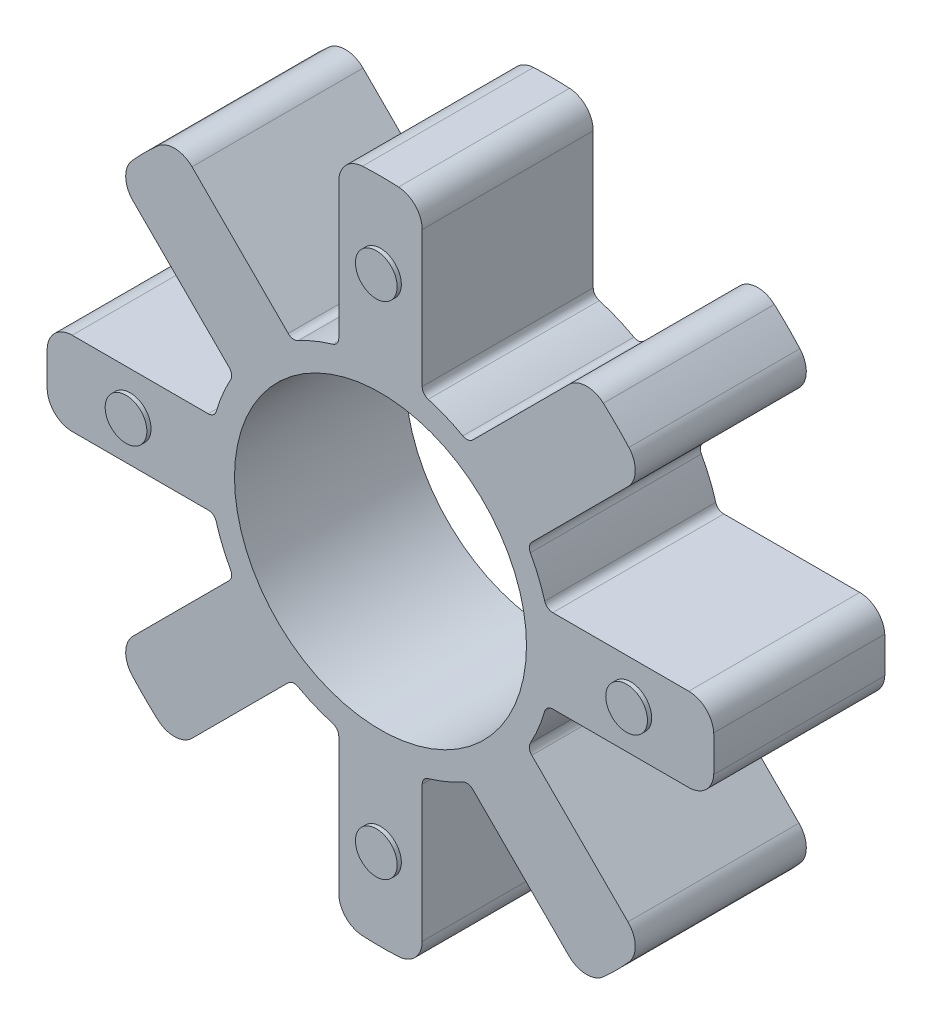
SolidWorks part; units mm, degrees
material "NEOPRENE"
ref_plane "Front Plane" through (0, 0, 0) normal (0, 0, 1) x (1, 0, 0)
ref_plane "Top Plane" through (0, 0, 0) normal (0, 1, 0) x (1, 0, 0)
ref_plane "Right Plane" through (0, 0, 0) normal (1, 0, 0) x (0, 0, -1)
sketch "Sketch1" plane through (0, 0, 0) normal (0, 0, 1) x (1, 0, 0)
  line L0 (-5, 20.6458) -> (-5, 36.9459)
  line L1 (5, 36.9459) -> (5, 20.6458)
  line L2 (0, 0) -> (0, 32.1317) construction
  line L3 (11.0633, 18.1343) -> (22.5892, 29.6602)
  line L4 (29.6602, 22.5892) -> (18.1343, 11.0633)
  line L5 (20.6458, 5) -> (36.9459, 5)
  line L6 (36.9459, -5) -> (20.6458, -5)
  line L7 (18.1343, -11.0633) -> (29.6602, -22.5892)
  line L8 (22.5892, -29.6602) -> (11.0633, -18.1343)
  line L9 (5, -20.6458) -> (5, -36.9459)
  line L10 (-5, -36.9459) -> (-5, -20.6458)
  line L11 (-11.0633, -18.1343) -> (-22.5892, -29.6602)
  line L12 (-29.6602, -22.5892) -> (-18.1343, -11.0633)
  line L13 (-20.6458, -5) -> (-36.9459, -5)
  line L14 (-36.9459, 5) -> (-20.6458, 5)
  line L15 (-18.1343, 11.0633) -> (-29.6602, 22.5892)
  line L16 (-22.5892, 29.6602) -> (-11.0633, 18.1343)
  line L17 (0, 0) -> (48.5575, 0) construction
  arc A0 (-39.9415, 2.1622) -> (-39.9415, -2.1622) centre (0, 0) ccw
  arc A1 (-17.9651, 9.8745) -> (-19.6856, 5.7209) centre (0, 0) ccw
  circle A2 centre (0, 0) radius 17.5
  arc A3 (-26.714, 29.7718) -> (-29.7718, 26.714) centre (0, 0) ccw
  arc A4 (2.1622, 39.9415) -> (-2.1622, 39.9415) centre (0, 0) ccw
  arc A5 (29.7718, 26.714) -> (26.714, 29.7718) centre (0, 0) ccw
  arc A6 (26.714, -29.7718) -> (29.7718, -26.714) centre (0, 0) ccw
  arc A7 (-2.1622, -39.9415) -> (2.1622, -39.9415) centre (0, 0) ccw
  arc A8 (-29.7718, -26.714) -> (-26.714, -29.7718) centre (0, 0) ccw
  arc A9 (39.9415, -2.1622) -> (39.9415, 2.1622) centre (0, 0) ccw
  arc A10 (-19.6856, -5.7209) -> (-17.9651, -9.8745) centre (0, 0) ccw
  arc A11 (-9.8745, -17.9651) -> (-5.7209, -19.6856) centre (0, 0) ccw
  arc A12 (5.7209, -19.6856) -> (9.8745, -17.9651) centre (0, 0) ccw
  arc A13 (17.9651, -9.8745) -> (19.6856, -5.7209) centre (0, 0) ccw
  arc A14 (19.6856, 5.7209) -> (17.9651, 9.8745) centre (0, 0) ccw
  arc A15 (9.8745, 17.9651) -> (5.7209, 19.6856) centre (0, 0) ccw
  arc A16 (-5.7209, 19.6856) -> (-9.8745, 17.9651) centre (0, 0) ccw
  arc A17 (-29.6602, 22.5892) -> (-29.7718, 26.714) centre (-27.5389, 24.7105) cw
  arc A18 (-22.5892, 29.6602) -> (-26.714, 29.7718) centre (-24.7105, 27.5389) ccw
  arc A19 (-36.9459, -5) -> (-39.9415, -2.1622) centre (-36.9459, -2) cw
  arc A20 (-36.9459, 5) -> (-39.9415, 2.1622) centre (-36.9459, 2) ccw
  arc A21 (-22.5892, -29.6602) -> (-26.714, -29.7718) centre (-24.7105, -27.5389) cw
  arc A22 (-29.6602, -22.5892) -> (-29.7718, -26.714) centre (-27.5389, -24.7105) ccw
  arc A23 (-5, -36.9459) -> (-2.1622, -39.9415) centre (-2, -36.9459) ccw
  arc A24 (5, -36.9459) -> (2.1622, -39.9415) centre (2, -36.9459) cw
  arc A25 (29.6602, -22.5892) -> (29.7718, -26.714) centre (27.5389, -24.7105) cw
  arc A26 (22.5892, -29.6602) -> (26.714, -29.7718) centre (24.7105, -27.5389) ccw
  arc A27 (36.9459, -5) -> (39.9415, -2.1622) centre (36.9459, -2) ccw
  arc A28 (36.9459, 5) -> (39.9415, 2.1622) centre (36.9459, 2) cw
  arc A29 (29.6602, 22.5892) -> (29.7718, 26.714) centre (27.5389, 24.7105) ccw
  arc A30 (22.5892, 29.6602) -> (26.714, 29.7718) centre (24.7105, 27.5389) cw
  arc A31 (5, 36.9459) -> (2.1622, 39.9415) centre (2, 36.9459) ccw
  arc A32 (-5, 36.9459) -> (-2.1622, 39.9415) centre (-2, 36.9459) cw
  arc A33 (-11.0633, 18.1343) -> (-9.8745, 17.9651) centre (-10.3562, 18.8414) ccw
  arc A34 (-5, 20.6458) -> (-5.7209, 19.6856) centre (-6, 20.6458) cw
  arc A35 (11.0633, 18.1343) -> (9.8745, 17.9651) centre (10.3562, 18.8414) cw
  arc A36 (5, 20.6458) -> (5.7209, 19.6856) centre (6, 20.6458) ccw
  arc A37 (20.6458, 5) -> (19.6856, 5.7209) centre (20.6458, 6) cw
  arc A38 (18.1343, 11.0633) -> (17.9651, 9.8745) centre (18.8414, 10.3562) ccw
  arc A39 (18.1343, -11.0633) -> (17.9651, -9.8745) centre (18.8414, -10.3562) cw
  arc A40 (20.6458, -5) -> (19.6856, -5.7209) centre (20.6458, -6) ccw
  arc A41 (11.0633, -18.1343) -> (9.8745, -17.9651) centre (10.3562, -18.8414) ccw
  arc A42 (5, -20.6458) -> (5.7209, -19.6856) centre (6, -20.6458) cw
  arc A43 (-5, -20.6458) -> (-5.7209, -19.6856) centre (-6, -20.6458) ccw
  arc A44 (-11.0633, -18.1343) -> (-9.8745, -17.9651) centre (-10.3562, -18.8414) cw
  arc A45 (-18.1343, -11.0633) -> (-17.9651, -9.8745) centre (-18.8414, -10.3562) ccw
  arc A46 (-20.6458, -5) -> (-19.6856, -5.7209) centre (-20.6458, -6) cw
  arc A47 (-20.6458, 5) -> (-19.6856, 5.7209) centre (-20.6458, 6) ccw
  arc A48 (-18.1343, 11.0633) -> (-17.9651, 9.8745) centre (-18.8414, 10.3562) cw
  point P40 (0, 0)
  point P71 (5, 39.6863)
  point P78 (-5, 19.8809)
  point P81 (10.5224, 17.5934)
  point P84 (5, 19.8809)
  dimension "D1" = 80
  dimension "D2" = 41
  dimension "D3" = 35
  dimension "D7" = 3
  dimension "D8" = 1
  dimension "D4" = 10
  dimension "D5" = 5
  dimension "D6" = 8
extrude "Boss-Extrude1" add sketch "Sketch1" along normal mid plane 20.5
sketch "Sketch2" plane through (0, 0, 10.25) normal (0, 0, 1) x (1, 0, 0)
  circle A0 centre (0, 0) radius 30 construction
  circle A1 centre (0, 30) radius 2.5
  dimension "D1" = 60
  dimension "D2" = 5
extrude "Boss-Extrude2" add sketch "Sketch2" along normal mid plane 1
sketch "Sketch3" plane through (0, 0, -10.25) normal (0, 0, -1) x (-1, 0, 0)
  line L0 (-28.2843, 28.2843) -> (0, 0) construction
  circle A0 centre (0, 0) radius 30 construction
  circle A1 centre (-21.2132, 21.2132) radius 2.5
  arc A2 (-26.714, 29.7718) -> (-29.7718, 26.714) centre (0, 0) ccw construction
  dimension "D1" = 60
  dimension "D2" = 5
extrude "Boss-Extrude3" add sketch "Sketch3" along normal mid plane 1
pattern_circular "CirPattern1" count 4 over 360 about axis through (0, 0, 0) along (0, 0, 1) of "Boss-Extrude2", "Boss-Extrude3"
